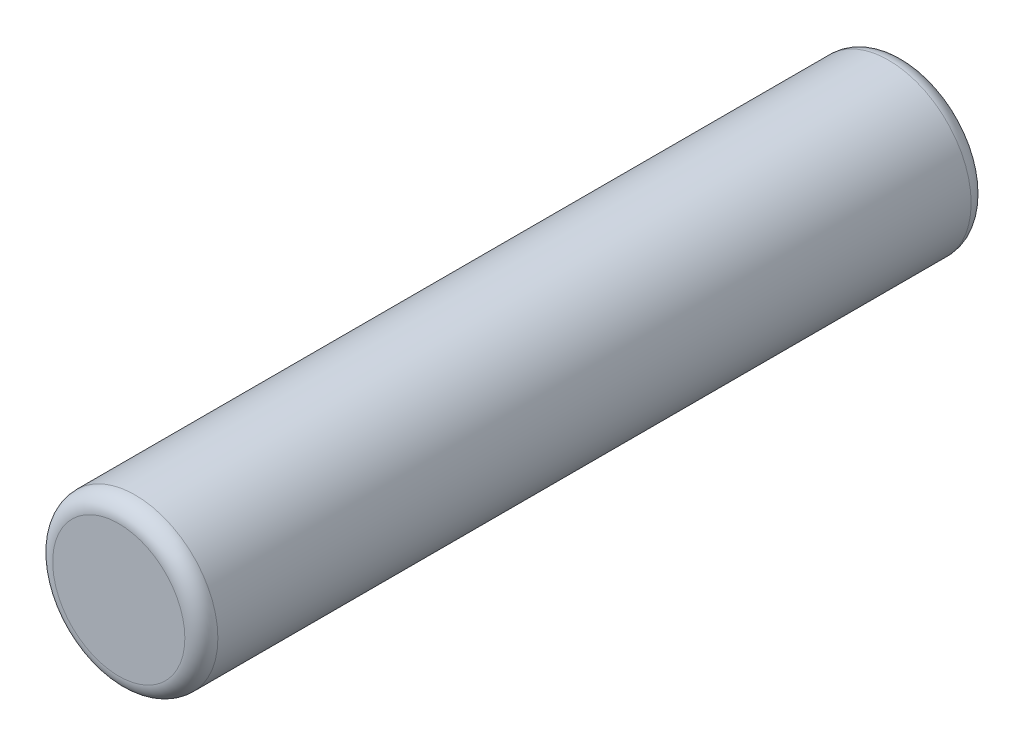
SolidWorks part; units mm, degrees
ref_plane "Plan1" through (0, 0, 0) normal (0, 0, 1) x (1, 0, 0)
ref_plane "Plan2" through (0, 0, 0) normal (0, 1, 0) x (1, 0, 0)
ref_plane "Plan3" through (0, 0, 0) normal (1, 0, 0) x (0, 0, -1)
sketch "Esquisse1" plane through (0, 0, 0) normal (0, 0, 1) x (1, 0, 0)
  circle A0 centre (0, 0) radius 2.5
  dimension "D1" = 5
extrude "Base-Extrusion" add sketch "Esquisse1" along normal blind 23.8
fillet "Congé1" radius 0.5
